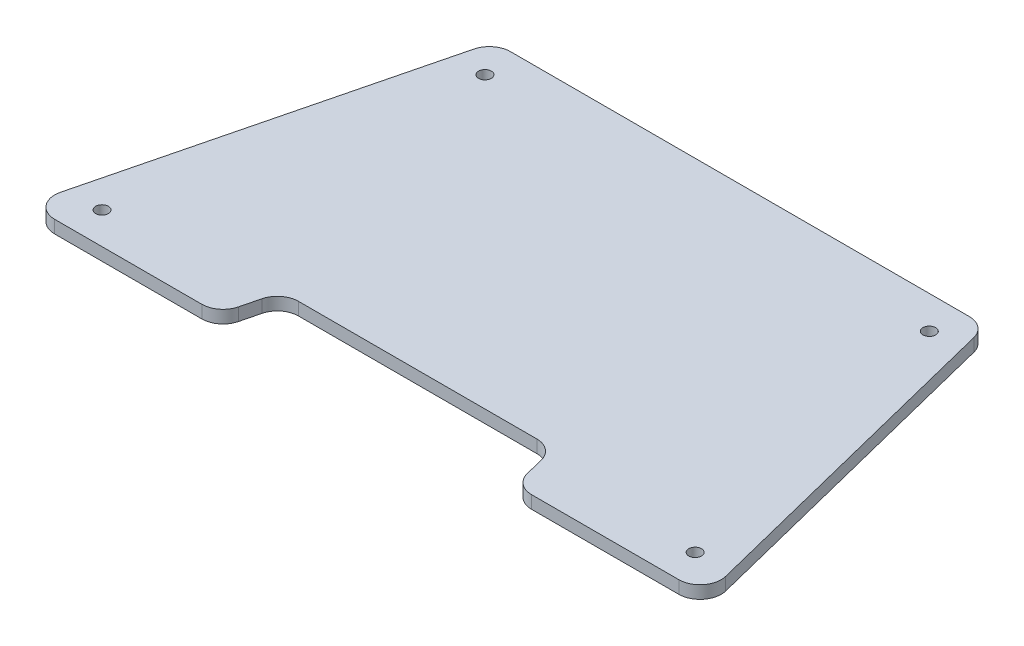
SolidWorks part; units mm, degrees
ref_plane "Ön Düzlem" through (0, 0, 0) normal (0, 0, 1) x (1, 0, 0)
ref_plane "Üst Düzlem" through (0, 0, 0) normal (0, 1, 0) x (1, 0, 0)
ref_plane "Sağ Düzlem" through (0, 0, 0) normal (1, 0, 0) x (0, 0, -1)
sketch "Çizim1" plane through (0, 0, 0) normal (0, 1, 0) x (1, 0, 0)
  line L0 (3.9039, 0) -> (112.0961, 0)
  line L1 (116.9468, -3.7873) -> (136.4468, -81.7873)
  line L2 (131.5961, -88) -> (96.9039, -88)
  line L3 (92.0532, -84.2127) -> (90.9468, -79.7873)
  line L4 (86.0961, -76) -> (29.9039, -76)
  line L5 (25.0532, -79.7873) -> (23.9468, -84.2127)
  line L6 (19.0961, -88) -> (-15.5961, -88)
  line L7 (-20.4468, -81.7873) -> (-0.9468, -3.7873)
  line L8 (58, 0) -> (58, -76) construction
  arc A0 (23.9468, -84.2127) -> (19.0961, -88) centre (19.0961, -83) cw
  arc A1 (96.9039, -88) -> (92.0532, -84.2127) centre (96.9039, -83) cw
  arc A2 (29.9039, -76) -> (25.0532, -79.7873) centre (29.9039, -81) ccw
  arc A3 (90.9468, -79.7873) -> (86.0961, -76) centre (86.0961, -81) ccw
  arc A4 (131.5961, -88) -> (136.4468, -81.7873) centre (131.5961, -83) ccw
  arc A5 (-15.5961, -88) -> (-20.4468, -81.7873) centre (-15.5961, -83) cw
  arc A6 (116.9468, -3.7873) -> (112.0961, 0) centre (112.0961, -5) ccw
  arc A7 (3.9039, 0) -> (-0.9468, -3.7873) centre (3.9039, -5) ccw
  point P18 (23, -88)
  point P21 (93, -88)
  point P28 (138, -88)
  point P31 (-22, -88)
  point P34 (116, 0)
  point P37 (0, 0)
  dimension "D6" = 5
  dimension "D7" = 5
  dimension "D1" = 116
  dimension "D2" = 160
  dimension "D3" = 76
  dimension "D4" = 12
  dimension "D5" = 45
extrude "Yükseklik-Ekstrüzyon1" add sketch "Çizim1" along normal blind 3
sketch "Çizim2" plane through (0, 3, 0) normal (0, 1, 0) x (1, 0, 0)
  line L2 (58, 0) -> (58, -76) construction
  line L3 (112.0961, 0) -> (3.9039, 0) construction
  line L4 (29.9039, -76) -> (86.0961, -76) construction
  circle A0 centre (5.6, -7.73) radius 1.5
  circle A2 centre (110.4, -7.73) radius 1.5
  dimension "D2" = 3
  dimension "D3" = 52.4
  dimension "D1" = 7.73
extrude "Kes-Ekstrüzyon1" cut sketch "Çizim2" against normal blind 10
sketch "Çizim4" plane through (0, 3, 0) normal (0, 1, 0) x (1, 0, 0)
  line L0 (-15.5961, -88) -> (19.0961, -88) construction
  line L1 (58, -76) -> (58, -28.1155) construction
  line L2 (29.9039, -76) -> (86.0961, -76) construction
  circle A0 centre (-11.94, -80.5) radius 1.5
  circle A1 centre (127.94, -80.5) radius 1.5
  point P4 (1.75, -88)
  dimension "D3" = 3
  dimension "D1" = 7.5
  dimension "D2" = 13.69
extrude "Kes-Ekstrüzyon2" cut sketch "Çizim4" against normal blind 10
